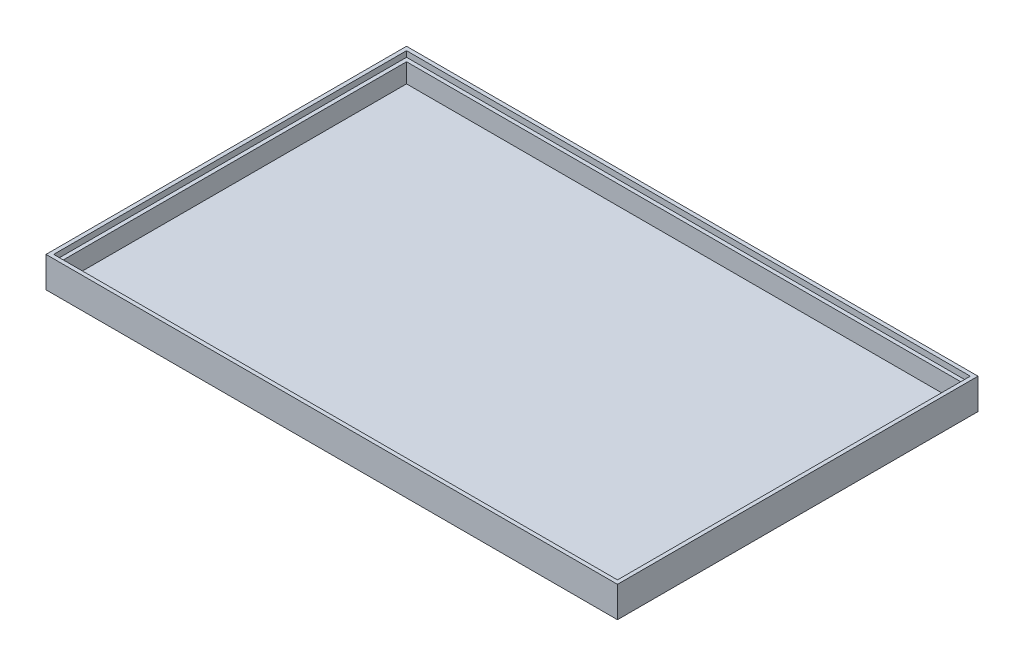
SolidWorks part; units mm, degrees
ref_plane "Front Plane" through (0, 0, 0) normal (0, 0, 1) x (1, 0, 0)
ref_plane "Top Plane" through (0, 0, 0) normal (0, 1, 0) x (1, 0, 0)
ref_plane "Right Plane" through (0, 0, 0) normal (1, 0, 0) x (0, 0, -1)
sketch "Sketch1" plane through (0, 0, 0) normal (0, 1, 0) x (1, 0, 0)
  line L1 (-72.5, -45) -> (72.5, -45)
  line L2 (-72.5, -45) -> (-72.5, 45)
  line L3 (-72.5, 45) -> (72.5, 45)
  line L4 (72.5, -45) -> (72.5, 45)
  line L5 (-72.5, -45) -> (72.5, 45) construction
  line L6 (-72.5, 45) -> (72.5, -45) construction
  point P0 (0, 0)
  dimension "D1" = 145
  dimension "D2" = 90
extrude "Boss-Extrude1" add sketch "Sketch1" along normal blind 1.5
sketch "Sketch2" plane through (0, 0, 0) normal (0, 1, 0) x (1, 0, 0)
  line L14 (-74.5, -47) -> (74.5, -47)
  line L15 (74.5, -47) -> (74.5, 47)
  line L16 (74.5, 47) -> (-74.5, 47)
  line L17 (-74.5, 47) -> (-74.5, -47)
  line L18 (-74.5, -47) -> (74.5, -47)
  line L19 (74.5, -47) -> (74.5, 47)
  line L20 (74.5, 47) -> (-74.5, 47)
  line L21 (-74.5, 47) -> (-74.5, -47)
  line L32 (-72.5, -45) -> (72.5, -45)
  line L33 (72.5, -45) -> (72.5, 45)
  line L34 (72.5, 45) -> (-72.5, 45)
  line L35 (-72.5, 45) -> (-72.5, -45)
  line L36 (-72.5, -45) -> (72.5, -45)
  line L37 (72.5, -45) -> (72.5, 45)
  line L38 (72.5, 45) -> (-72.5, 45)
  line L39 (-72.5, 45) -> (-72.5, -45)
  dimension "D1" = 2
  dimension "D2" = 0
extrude "Boss-Extrude2" add sketch "Sketch2" along normal blind 8
sketch "Sketch3" plane through (0, 8, 0) normal (0, 1, 0) x (1, 0, 0)
  line L8 (-73.5, 46) -> (-73.5, -46)
  line L9 (-73.5, -46) -> (73.5, -46)
  line L10 (73.5, -46) -> (73.5, 46)
  line L11 (73.5, 46) -> (-73.5, 46)
  line L12 (-73.5, 46) -> (-73.5, -46)
  line L13 (-73.5, -46) -> (73.5, -46)
  line L14 (73.5, -46) -> (73.5, 46)
  line L15 (73.5, 46) -> (-73.5, 46)
  line L26 (-72.5, -45) -> (72.5, -45)
  line L27 (72.5, -45) -> (72.5, 45)
  line L28 (72.5, 45) -> (-72.5, 45)
  line L29 (-72.5, 45) -> (-72.5, -45)
  line L30 (-72.5, -45) -> (72.5, -45)
  line L31 (72.5, -45) -> (72.5, 45)
  line L32 (72.5, 45) -> (-72.5, 45)
  line L33 (-72.5, 45) -> (-72.5, -45)
  dimension "D1" = 1
  dimension "D2" = 0
extrude "Cut-Extrude1" cut sketch "Sketch3" against normal blind 1.5
